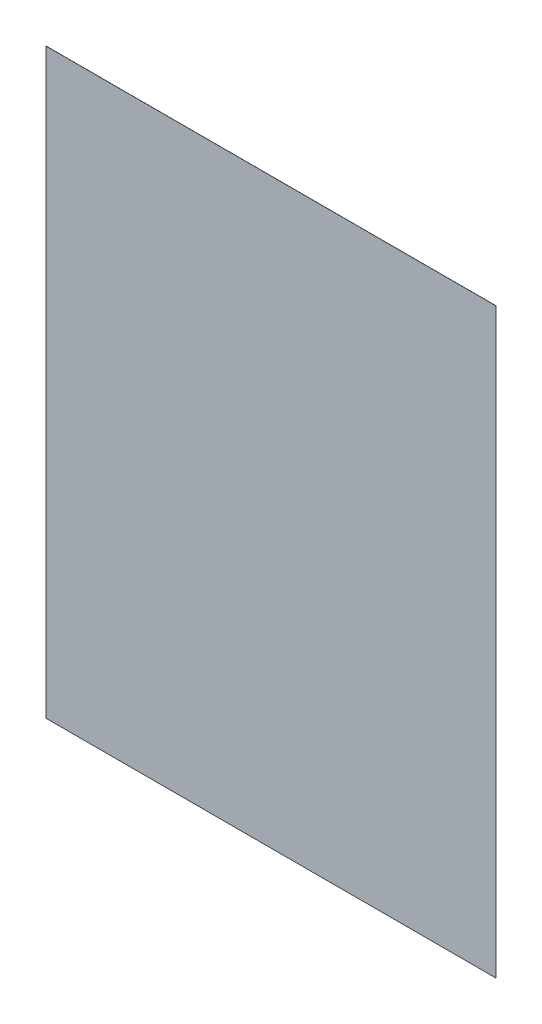
SolidWorks part; units mm, degrees
ref_plane "Front Plane" through (0, 0, 0) normal (0, 0, 1) x (1, 0, 0)
ref_plane "Top Plane" through (0, 0, 0) normal (0, 1, 0) x (1, 0, 0)
ref_plane "Right Plane" through (0, 0, 0) normal (1, 0, 0) x (0, 0, -1)
sketch "Sketch1" plane through (0, 0, 0) normal (0, 0, 1) x (1, 0, 0)
  line L0 (-107.95, 139.7) -> (107.95, -139.7) construction
  line L1 (-107.95, 139.7) -> (107.95, 139.7)
  line L2 (-107.95, 139.7) -> (-107.95, -139.7)
  line L3 (-107.95, -139.7) -> (107.95, -139.7)
  line L4 (107.95, 139.7) -> (107.95, -139.7)
  dimension "D1" = 279.4
  dimension "D2" = 215.9
extrude "Boss-Extrude1" add sketch "Sketch1" along normal blind 0.05
